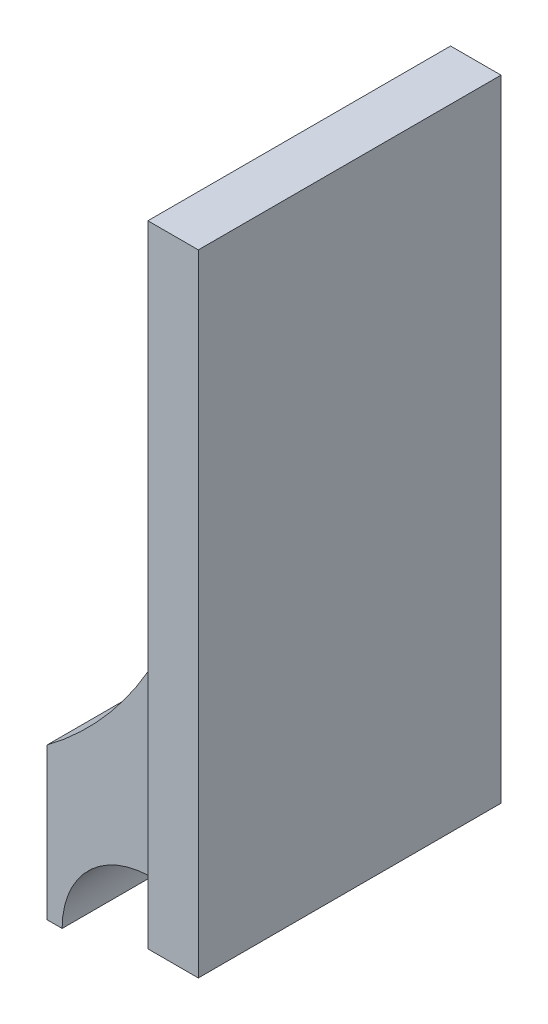
SolidWorks part; units mm, degrees
ref_plane "Front Plane" through (0, 0, 0) normal (0, 0, 1) x (1, 0, 0)
ref_plane "Top Plane" through (0, 0, 0) normal (0, 1, 0) x (1, 0, 0)
ref_plane "Right Plane" through (0, 0, 0) normal (1, 0, 0) x (0, 0, -1)
sketch "Sketch1" plane through (0, 0, 0) normal (1, 0, 0) x (0, 0, -1)
  line L1 (-6, -12.5) -> (6, -12.5)
  line L2 (-6, -12.5) -> (-6, 12.5)
  line L3 (-6, 12.5) -> (6, 12.5)
  line L4 (6, -12.5) -> (6, 12.5)
  line L5 (-6, -12.5) -> (6, 12.5) construction
  line L6 (-6, 12.5) -> (6, -12.5) construction
  point P0 (0, 0)
  dimension "D1" = 12
  dimension "D2" = 25
extrude "Boss-Extrude1" add sketch "Sketch1" along normal blind 2
sketch "Sketch2" plane through (0, 0, 6) normal (0, 0, 1) x (1, 0, 0)
  line L0 (-6, -9.5) -> (-6, -15.5)
  line L1 (0, 12.5) -> (0, -12.5) construction
  line L2 (2, -12.5) -> (0, -12.5) construction
  line L3 (0, 2.5) -> (0, -12.5)
  line L4 (-6, -15.5) -> (-5.4, -15.5)
  line L5 (-5.4, -15.5) -> (-5.4, -18.8718) construction
  arc A1 (-6, -9.5) -> (0, 2.5) centre (-15, 2.5) ccw
  arc A2 (-5.4, -15.5) -> (0, -12.5) centre (-1.8667, -15.5) cw
  dimension "D4" = 15
  dimension "D1" = 6
  dimension "D2" = 6
  dimension "D3" = 3
  dimension "D5" = 0.6
extrude "Boss-Extrude2" add sketch "Sketch2" against normal up to surface (12 mm away) up to face at (1, 0, -6)
sketch "Sketch3" plane through (-6, 0, 0) normal (-1, 0, 0) x (0, 0, 1)
  line L1 (-4, 17.6977) -> (4, 17.6977)
  line L2 (-4, 17.6977) -> (-4, -17.6977)
  line L3 (-4, -17.6977) -> (4, -17.6977)
  line L4 (4, 17.6977) -> (4, -17.6977)
  line L5 (-4, 17.6977) -> (4, -17.6977) construction
  line L6 (-4, -17.6977) -> (4, 17.6977) construction
  line L7 (-11.5235, 20.567) -> (11.5235, 20.567)
  line L8 (-11.5235, 20.567) -> (-11.5235, -20.567)
  line L9 (-11.5235, -20.567) -> (11.5235, -20.567)
  line L10 (11.5235, 20.567) -> (11.5235, -20.567)
  line L11 (-11.5235, 20.567) -> (11.5235, -20.567) construction
  line L12 (-11.5235, -20.567) -> (11.5235, 20.567) construction
  point P0 (0, 0)
  point P6 (0, 0)
  dimension "D1" = 8
extrude "Cut-Extrude1" cut sketch "Sketch3" against normal up to surface (6 mm away) up to face at (0, 7.5, 0)
